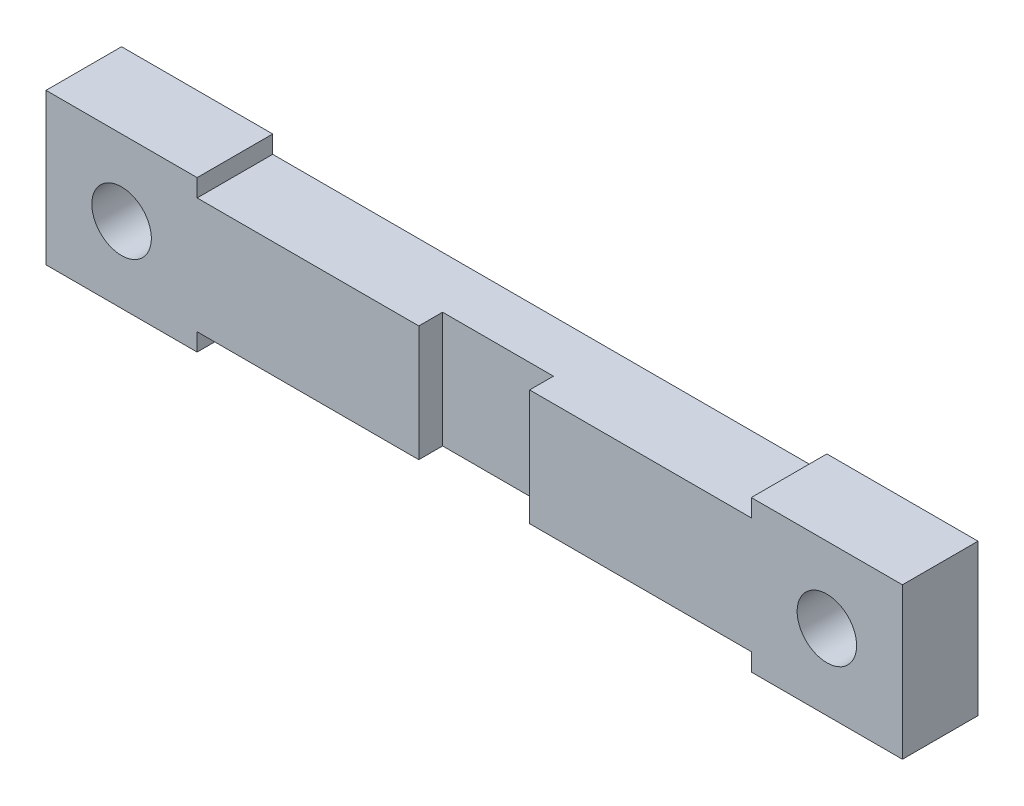
SolidWorks part; units mm, degrees
ref_plane "Front Plane" through (0, 0, 0) normal (0, 0, 1) x (1, 0, 0)
ref_plane "Top Plane" through (0, 0, 0) normal (0, 1, 0) x (1, 0, 0)
ref_plane "Right Plane" through (0, 0, 0) normal (1, 0, 0) x (0, 0, -1)
sketch "Sketch1" plane through (0, 0, 0) normal (0, 0, 1) x (1, 0, 0)
  line L0 (0, 2.921) -> (0, -2.921) construction
  line L1 (-13.97, -2.921) -> (13.97, -2.921)
  line L2 (-13.97, -2.921) -> (-13.97, 2.921)
  line L3 (-13.97, 2.921) -> (13.97, 2.921)
  line L4 (13.97, -2.921) -> (13.97, 2.921)
  line L5 (-13.97, -2.921) -> (13.97, 2.921) construction
  line L6 (-13.97, 2.921) -> (13.97, -2.921) construction
  line L7 (21.59, 0) -> (13.97, 0) construction
  line L8 (13.97, 3.81) -> (21.59, 3.81)
  line L9 (13.97, 3.81) -> (13.97, -3.81)
  line L10 (13.97, -3.81) -> (21.59, -3.81)
  line L11 (21.59, 3.81) -> (21.59, -3.81)
  line L12 (-13.97, -3.81) -> (-21.59, -3.81)
  line L13 (-21.59, 3.81) -> (-21.59, -3.81)
  line L14 (-13.97, 3.81) -> (-21.59, 3.81)
  line L15 (-13.97, 3.81) -> (-13.97, -3.81)
  circle A0 centre (17.78, 0) radius 1.5
  circle A1 centre (-17.78, 0) radius 1.5
  circle A2 centre (0, 0) radius 17.78 construction
  point P0 (0, 0)
  dimension "D1" = 3
  dimension "D2" = 35.56
  dimension "D3" = 3.81
  dimension "D4" = 3.81
  dimension "D5" = 5.842
extrude "Boss-Extrude1" add sketch "Sketch1" along normal blind 3.81 contours L15 L14 L13 L12 L2 A1 | L1 L4 L3 L2 | L11 L8 L9 L4 L10 A0
sketch "Sketch2" plane through (0, 0, 3.81) normal (0, 0, 1) x (1, 0, 0)
  line L0 (-13.97, 2.921) -> (13.97, 2.921) construction
  line L1 (-2.794, -2.921) -> (2.794, -2.921)
  line L2 (-2.794, -2.921) -> (-2.794, 2.921)
  line L3 (-2.794, 2.921) -> (2.794, 2.921)
  line L4 (2.794, -2.921) -> (2.794, 2.921)
  line L5 (-2.794, -2.921) -> (2.794, 2.921) construction
  line L6 (-2.794, 2.921) -> (2.794, -2.921) construction
  point P0 (0, 0)
  dimension "D1" = 5.588
extrude "Cut-Extrude1" cut sketch "Sketch2" against normal blind 1.2
